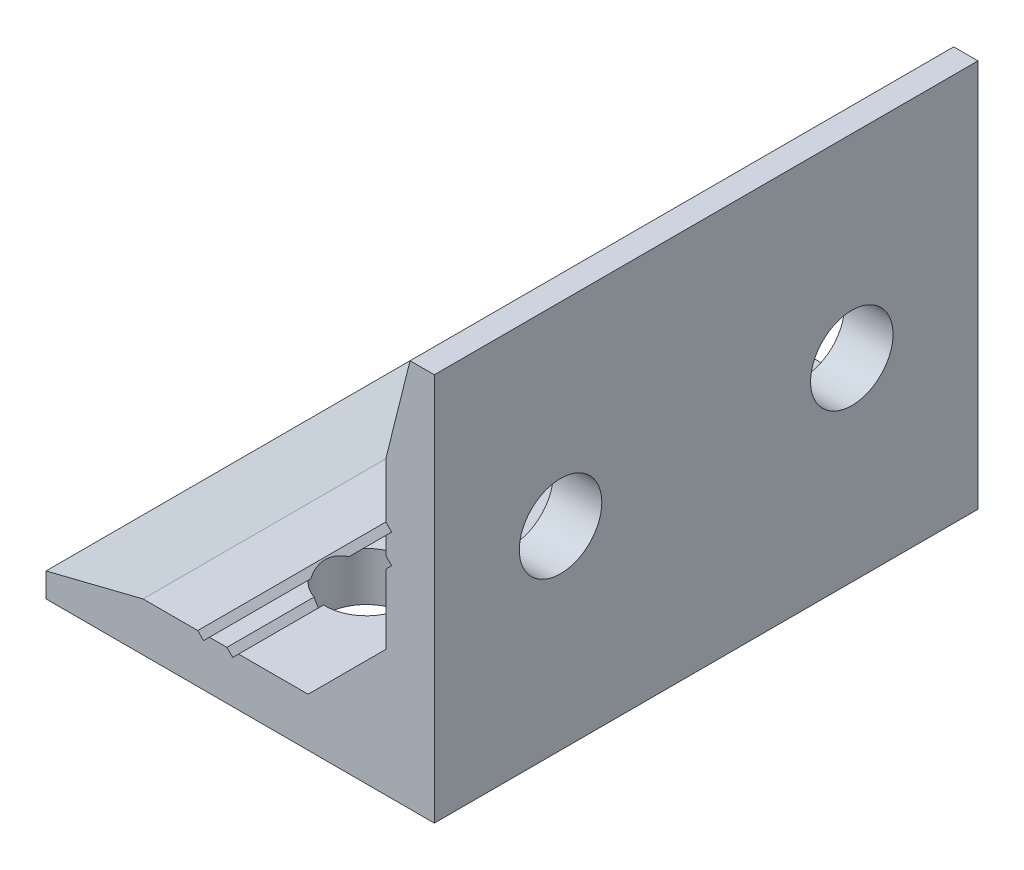
SolidWorks part; units mm, degrees
ref_plane "前视基准面" through (0, 0, 0) normal (0, 0, 1) x (1, 0, 0)
ref_plane "上视基准面" through (0, 0, 0) normal (0, 1, 0) x (1, 0, 0)
ref_plane "右视基准面" through (0, 0, 0) normal (1, 0, 0) x (0, 0, -1)
sketch "草图1" plane through (0, 0, 0) normal (0, 0, 1) x (1, 0, 0)
  line B0 (0, 0) -> (40, 0)
  line B1 (40, 0) -> (40, 40)
  line B2 (10, 5) -> (15.635, 5)
  line B3 (16.835, 5) -> (18.635, 5)
  line B4 (19.835, 5) -> (27, 5)
  line B5 (35, 13) -> (35, 20.165)
  line B6 (35, 21.365) -> (35, 23.165)
  line B7 (35, 24.365) -> (35, 30)
  line B8 (0, 2.5) -> (0, 0)
  line B9 (37.5, 40) -> (40, 40)
  line B10 (0, 2.5) -> (10, 5)
  line B11 (37.5, 40) -> (35, 30)
  line B12 (27, 5) -> (35, 13)
  line B13 (16.235, 4.4) -> (15.635, 5)
  line B14 (16.235, 4.4) -> (16.835, 5)
  line B15 (19.235, 4.4) -> (18.635, 5)
  line B16 (19.235, 4.4) -> (19.835, 5)
  line B17 (35.6, 23.765) -> (35, 24.365)
  line B18 (35.6, 23.765) -> (35, 23.165)
  line B19 (35.6, 20.765) -> (35, 21.365)
  line B20 (35.6, 20.765) -> (35, 20.165)
sketch_block_instance "A$C2EE5613F-1"
sketch_block "A$C2EE5613F"
extrude "凸台-拉伸1" add sketch "草图1" along normal mid plane 56
sketch "草图3" plane through (0, 5, 0) normal (0, 1, 0) x (1, 0, 0)
  line L0 (0, 0) -> (24.6159, 0) construction
  line L1 (0, -28) -> (0, 28) construction
  circle A0 centre (20, 15) radius 4.25
  circle A1 centre (20, -15) radius 4.25
  dimension "D1" = 20
  dimension "D2" = 15
extrude "切除-拉伸1" cut sketch "草图3" against normal through all
sketch "草图4" plane through (11, -11, 0) normal (-0.7071, 0.7071, 0) x (0, 0, 1)
  line L0 (28, 28.2843) -> (-28, 28.2843) construction
  line L1 (28, 33.9411) -> (28, 22.6274) construction
  line L2 (-28, 33.9411) -> (-28, 22.6274) construction
ref_plane "基准面2" through (20, 20, 0) normal (-0.7071, -0.7071, 0) x (-0.7071, 0.7071, 0)
mirror "镜向1" about plane through (20, 20, 0) normal (-0.7071, -0.7071, 0) of "切除-拉伸1"
